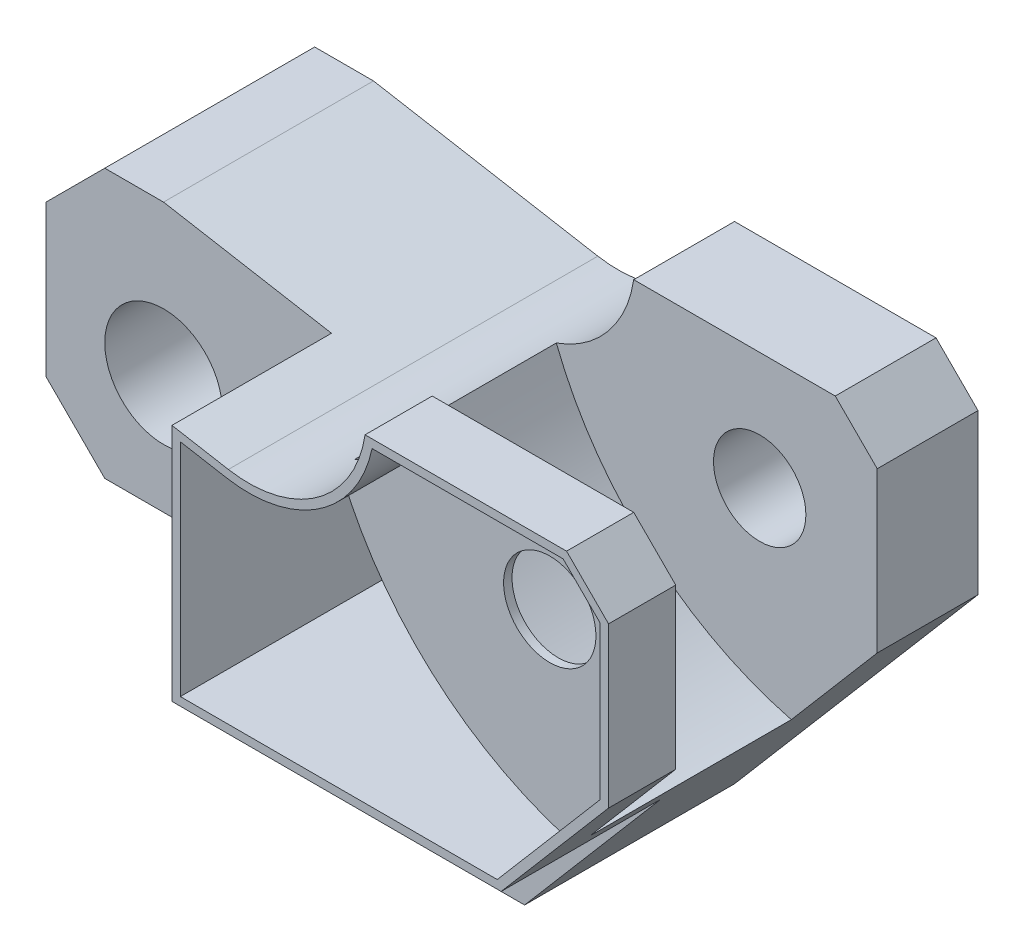
SolidWorks part; units mm, degrees
material "AISI 1020"
ref_plane "Front Plane" through (0, 0, 0) normal (0, 0, 1) x (1, 0, 0)
ref_plane "Top Plane" through (0, 0, 0) normal (0, 1, 0) x (1, 0, 0)
ref_plane "Right Plane" through (0, 0, 0) normal (1, 0, 0) x (0, 0, -1)
other "Center of Mass"
sketch "Sketch1" plane through (0, 0, 0) normal (0, 0, 1) x (1, 0, 0)
  line L0 (-79.9804, 23.3665) -> (-79.9804, 5.3665)
  line L1 (-72.9804, 30.3665) -> (-65.9804, 30.3665)
  line L2 (-72.9804, -1.6335) -> (-40.4049, -1.6335)
  line L3 (-72.9804, 30.3665) -> (-79.9804, 23.3665)
  line L8 (-79.9804, 23.3665) -> (-79.9804, 55.1551) construction
  line L9 (-79.9804, 5.3665) -> (-72.9804, -1.6335)
  line L10 (-79.9804, 5.3665) -> (-79.9804, -51.1023) construction
  line L11 (-65.9804, 30.3665) -> (-39.2569, 25.6544)
  line L12 (-65.9804, 30.3665) -> (-36.6575, 30.3665) construction
  line L13 (-22.9804, 37.3665) -> (1.0196, 37.3665)
  line L14 (1.0196, 37.3665) -> (6.0196, 32.3665)
  line L15 (6.0196, 32.3665) -> (6.0196, 13.3665)
  line L16 (6.0196, 13.3665) -> (-22.9804, -20.6335)
  line L17 (-28.6835, -20.6335) -> (-22.9804, -20.6335)
  circle A0 centre (-65.9804, 12.3665) radius 7
  arc A1 (-39.2569, 25.6544) -> (-22.9804, 37.3665) centre (-36.8258, 39.4417) ccw
  arc A2 (-40.4049, -1.6335) -> (-35.4593, -5.8982) centre (-40.4049, -6.6335) cw
  arc A5 (-35.4593, -5.8982) -> (-28.6835, -20.6335) centre (-6.7746, -1.6335) ccw
  arc A7 (-28.6835, -20.6335) -> (-35.4593, -5.8982) centre (-6.7746, -1.6335) cw
  point P2 (-79.9804, 30.3665)
  point P3 (-79.9804, -1.6335)
  point P20 (6.0196, 37.3665)
  point P21 (0, 0)
  point P23 (0, 0)
  point P25 (-17.9587, -28.9994)
  point P27 (0, 0)
  point P28 (-33.1885, -21.6663)
  point P30 (-40.0524, -6.2613)
  dimension "D7" = 14
  dimension "D10" = 14
  dimension "D15" = 5
  dimension "D16" = 29
  dimension "D4" = 32
  dimension "D3" = 7
  dimension "D1" = 45
  dimension "D2" = 45
  dimension "D6" = 14
  dimension "D8" = 14
  dimension "D9" = 10
  dimension "D11" = 29
  dimension "D12" = 24
  dimension "D14" = 29
  dimension "D17" = 45.2764
  dimension "D18" = 19
  dimension "D19" = 14
  dimension "D20" = 86
  dimension "D21" = 58
  dimension "D22" = 19
extrude "Boss-Extrude1" add sketch "Sketch1" along normal blind 44 contours A2 A5 L17 L16 L15 L14 L13 A1 L11 L1 L3 L0 L9 L2 A0
sketch "Sketch2" plane through (0, 0, 44) normal (0, 0, 1) x (1, 0, 0)
  line L0 (-22.9804, 37.3665) -> (1.0196, 37.3665) construction
  line L1 (6.0196, 32.3665) -> (6.0196, 13.3665) construction
  circle A0 centre (-7.9804, 23.3665) radius 5.5
  dimension "D1" = 11
  dimension "D2" = 14
  dimension "D3" = 14
extrude "Cut-Extrude1" cut sketch "Sketch2" against normal through all
sketch "Sketch3" plane through (0, 0, 44) normal (0, 0, 1) x (1, 0, 0)
  line L0 (-45.9804, 26.84) -> (-45.9804, -1.6335)
  line L4 (6.0196, 32.3665) -> (6.0196, 13.3665) construction
  line L5 (-72.9804, -1.6335) -> (-40.4049, -1.6335) construction
  line L6 (-79.9804, 5.3665) -> (-72.9804, -1.6335) construction
  line L7 (-79.9804, 23.3665) -> (-79.9804, 5.3665) construction
  line L8 (-72.9804, 30.3665) -> (-79.9804, 23.3665) construction
  line L9 (-72.9804, 30.3665) -> (-65.9804, 30.3665) construction
  line L10 (-65.9804, 30.3665) -> (-39.2569, 25.6544) construction
  line L11 (-72.9804, -1.6335) -> (-45.9804, -1.6335)
  line L12 (-79.9804, 5.3665) -> (-72.9804, -1.6335)
  line L13 (-79.9804, 23.3665) -> (-79.9804, 5.3665)
  line L14 (-72.9804, 30.3665) -> (-79.9804, 23.3665)
  line L15 (-72.9804, 30.3665) -> (-65.9804, 30.3665)
  line L16 (-65.9804, 30.3665) -> (-45.9804, 26.84)
  line L17 (-40.4049, -1.6335) -> (-6.7746, -1.6335)
  line L18 (6.0196, 13.3665) -> (-22.9804, -20.6335) construction
  line L20 (-28.6835, -20.6335) -> (-22.9804, -20.6335) construction
  line L21 (-6.7746, -1.6335) -> (-22.9804, -20.6335)
  line L22 (-28.6835, -20.6335) -> (-22.9804, -20.6335)
  arc A0 (-35.4593, -5.8982) -> (-28.6835, -20.6335) centre (-6.7746, -1.6335) ccw construction
  arc A1 (-35.4593, -5.8982) -> (-40.4049, -1.6335) centre (-40.4049, -6.6335) ccw construction
  arc A2 (-35.4593, -5.8982) -> (-28.6835, -20.6335) centre (-6.7746, -1.6335) ccw
  arc A3 (-35.4593, -5.8982) -> (-40.4049, -1.6335) centre (-40.4049, -6.6335) ccw
  dimension "D1" = 52
extrude "Cut-Extrude2" cut sketch "Sketch3" against normal blind 19
ref_plane "Plane1" through (0, 0, 12) normal (0, 0, -1) x (-1, 0, 0)
sketch "Sketch7" plane through (0, 0, 12) normal (0, 0, -1) x (-1, 0, 0)
  line L0 (-6.0196, 13.3665) -> (22.9804, -20.6335) construction
  line L1 (22.9804, 37.3665) -> (-1.0196, 37.3665) construction
  line L2 (-1.0196, 37.3665) -> (-6.0196, 32.3665) construction
  line L3 (-6.0196, 32.3665) -> (-6.0196, 13.3665) construction
  line L4 (-6.0196, 13.3665) -> (4.2157, 1.3665)
  line L5 (22.9804, 37.3665) -> (-1.0196, 37.3665)
  line L6 (-1.0196, 37.3665) -> (-6.0196, 32.3665)
  line L7 (-6.0196, 32.3665) -> (-6.0196, 13.3665)
  line L8 (-6.0196, 32.3665) -> (-6.0196, 49.7702) construction
  arc A0 (4.2157, 1.3665) -> (32.2003, 26.2279) centre (-6.0196, 41.0684) ccw
  arc A1 (22.9804, 37.3665) -> (39.2569, 25.6544) centre (36.8258, 39.4417) ccw construction
  arc A2 (22.9804, 37.3665) -> (32.2003, 26.2279) centre (36.8258, 39.4417) ccw
  point P1 (-6.0196, 41.2598)
  dimension "D1" = 82
  dimension "D2" = 36
extrude "Cut-Extrude3" cut sketch "Sketch7" against normal blind 24
sketch "Sketch8" plane through (0, 0, 44) normal (0, 0, 1) x (1, 0, 0)
  line L0 (-44.9804, 25.6482) -> (-44.9804, -0.6335)
  line L1 (-44.9804, -0.6335) -> (-7.236, -0.6335)
  line L2 (-7.236, -0.6335) -> (5.0196, 13.735)
  line L3 (5.0196, 13.735) -> (5.0196, 31.9523)
  line L4 (5.0196, 31.9523) -> (0.6053, 36.3665)
  line L5 (0.6053, 36.3665) -> (-22.1444, 36.3665)
  line L6 (-39.4305, 24.6696) -> (-44.9804, 25.6482)
  line L7 (-45.9804, -1.6335) -> (-6.7746, -1.6335)
  line L8 (-6.7746, -1.6335) -> (6.0196, 13.3665)
  line L9 (6.0196, 13.3665) -> (6.0196, 32.3665)
  line L10 (6.0196, 32.3665) -> (1.0196, 37.3665)
  line L11 (1.0196, 37.3665) -> (-22.9804, 37.3665)
  line L12 (-39.2569, 25.6544) -> (-45.9804, 26.84)
  line L13 (-45.9804, 26.84) -> (-45.9804, -1.6335)
  line L14 (-45.9804, -1.6335) -> (-6.7746, -1.6335)
  line L15 (-6.7746, -1.6335) -> (6.0196, 13.3665)
  line L16 (6.0196, 13.3665) -> (6.0196, 32.3665)
  line L17 (6.0196, 32.3665) -> (1.0196, 37.3665)
  line L18 (1.0196, 37.3665) -> (-22.9804, 37.3665)
  line L19 (-39.2569, 25.6544) -> (-45.9804, 26.84)
  line L20 (-45.9804, 26.84) -> (-45.9804, -1.6335)
  arc A0 (-39.4305, 24.6696) -> (-22.1444, 36.3665) centre (-36.8258, 39.4417) ccw
  arc A1 (-39.2569, 25.6544) -> (-22.9804, 37.3665) centre (-36.8258, 39.4417) ccw
  arc A2 (-39.2569, 25.6544) -> (-22.9804, 37.3665) centre (-36.8258, 39.4417) ccw
  dimension "D1" = 0
  dimension "D2" = 1
extrude "Cut-Extrude4" cut sketch "Sketch8" against normal blind 7 contours L0 L1 L2 L3 L4 L5 A0 L6
sketch "Sketch12" plane through (0, 0, 37) normal (0, 0, 1) x (1, 0, 0)
  line L0 (-7.236, -0.6335) -> (5.0196, 13.735) construction
  line L1 (-7.236, -0.6335) -> (-5.9936, 0.8231)
  line L7 (-39.4305, 24.6696) -> (-44.9804, 25.6482)
  line L8 (-44.9804, 25.6482) -> (-44.9804, -0.6335)
  line L9 (-44.9804, -0.6335) -> (-7.236, -0.6335)
  line L10 (-7.236, -0.6335) -> (5.0196, 13.735)
  line L11 (5.0196, 13.735) -> (5.0196, 31.9523)
  line L12 (5.0196, 31.9523) -> (0.6053, 36.3665)
  line L13 (0.6053, 36.3665) -> (-22.1444, 36.3665)
  line L14 (-39.4305, 24.6696) -> (-44.9804, 25.6482)
  line L15 (-44.9804, 25.6482) -> (-44.9804, -0.6335)
  line L16 (-44.9804, -0.6335) -> (-7.236, -0.6335)
  arc A1 (-39.4305, 24.6696) -> (-22.1444, 36.3665) centre (-36.8258, 39.4417) ccw
  arc A4 (-39.4305, 24.6696) -> (-22.1444, 36.3665) centre (-36.8258, 39.4417) ccw construction
  arc A5 (-39.4305, 24.6696) -> (-32.7838, 24.9966) centre (-36.8258, 39.4417) ccw
  arc A6 (-32.7838, 24.9966) -> (-5.9936, 0.8231) centre (6.0196, 41.0684) ccw
  dimension "D1" = 0
extrude "Cut-Extrude5" cut sketch "Sketch12" against normal blind 25 contours L14 L15 L16 L1 A6 A5
equation "\"A\" = 84mm"
equation "\"B\" = 59mm"
equation "\"C\"= 45mm"
